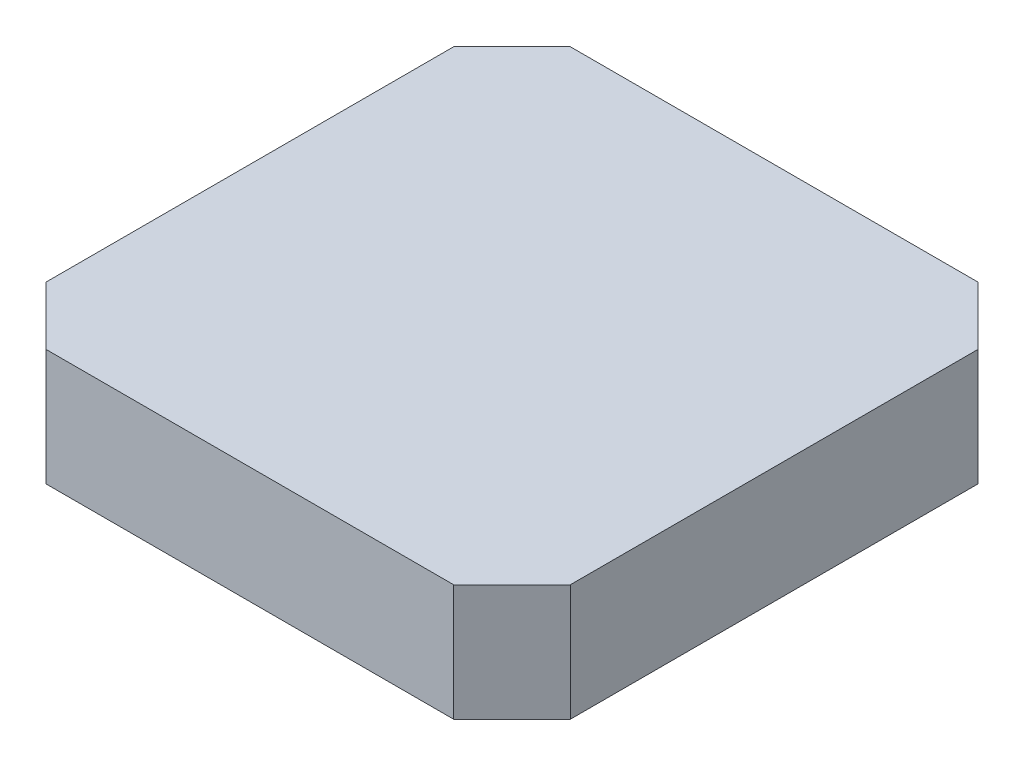
SolidWorks part; units mm, degrees
material "Polyurethane Foam Rigid"
ref_plane "Front Plane" through (0, 0, 0) normal (0, 0, 1) x (1, 0, 0)
ref_plane "Top Plane" through (0, 0, 0) normal (0, 1, 0) x (1, 0, 0)
ref_plane "Right Plane" through (0, 0, 0) normal (1, 0, 0) x (0, 0, -1)
sketch "Sketch1" plane through (0, 0, 0) normal (0, 1, 0) x (1, 0, 0)
  line L1 (-57.15, -57.15) -> (57.15, -57.15)
  line L2 (-57.15, -57.15) -> (-57.15, 57.15)
  line L3 (-57.15, 57.15) -> (57.15, 57.15)
  line L4 (57.15, -57.15) -> (57.15, 57.15)
  line L5 (-57.15, -57.15) -> (57.15, 57.15) construction
  line L6 (-57.15, 57.15) -> (57.15, -57.15) construction
  point P0 (0, 0)
  dimension "D1" = 114.3
  dimension "D2" = 114.3
extrude "Boss-Extrude1" add sketch "Sketch1" along normal blind 25.4
chamfer "Chamfer1" distance 12.7 angle 45 4 edges at (-57.15, 12.7, 57.15) (-57.15, 12.7, -57.15) (57.15, 12.7, -57.15) (57.15, 12.7, 57.15)
sketch "Sketch2" plane through (0, 0, 0) normal (0, -1, 0) x (-1, 0, 0)
  line L0 (44.45, -57.15) -> (-44.45, -57.15) construction
  circle A0 centre (0, -47.625) radius 6.35
  dimension "D2" = 12.7
  dimension "D1" = 9.525
extrude "Cut-Extrude1" cut sketch "Sketch2" against normal blind 5.08 contours A0
